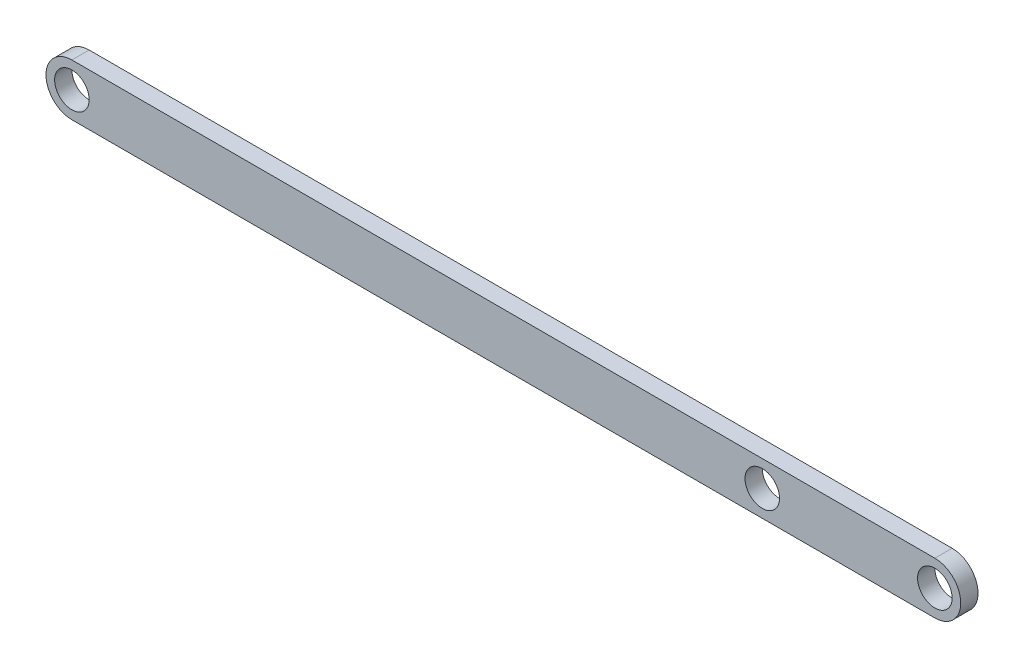
SolidWorks part; units mm, degrees
ref_plane "Спереди" through (0, 0, 0) normal (0, 0, 1) x (1, 0, 0)
ref_plane "Сверху" through (0, 0, 0) normal (0, 1, 0) x (1, 0, 0)
ref_plane "Справа" through (0, 0, 0) normal (1, 0, 0) x (0, 0, -1)
sketch "Эскиз1" plane through (0, 0, 0) normal (0, 0, 1) x (1, 0, 0)
  line L0 (0, 0) -> (-500, 0)
  line L1 (0, 30) -> (-500, 30)
  arc A0 (0, 0) -> (0, 30) centre (0, 15) ccw
  arc A1 (-500, 30) -> (-500, 0) centre (-500, 15) ccw
  dimension "D1" = 500
  dimension "D2" = 30
extrude "Бобышка-Вытянуть2" add sketch "Эскиз1" along normal blind 10 contours A1 L0 A0 L1
sketch "Эскиз2" plane through (0, 0, 0) normal (0, 0, -1) x (-1, 0, 0)
  circle A0 centre (0, 15) radius 10
  circle A1 centre (500, 15) radius 10
  dimension "D1" = 20
  dimension "D2" = 20
extrude "Вырез-Вытянуть1" cut sketch "Эскиз2" against normal blind 10
sketch "Эскиз3" plane through (0, 0, 10) normal (0, 0, 1) x (1, 0, 0)
  circle A0 centre (-100, 15) radius 10
  circle A1 centre (0, 15) radius 10 construction
  circle A2 centre (0, 15) radius 10 construction
  dimension "D1" = 100
extrude "Вырез-Вытянуть2" cut sketch "Эскиз3" against normal blind 10 contours A0
